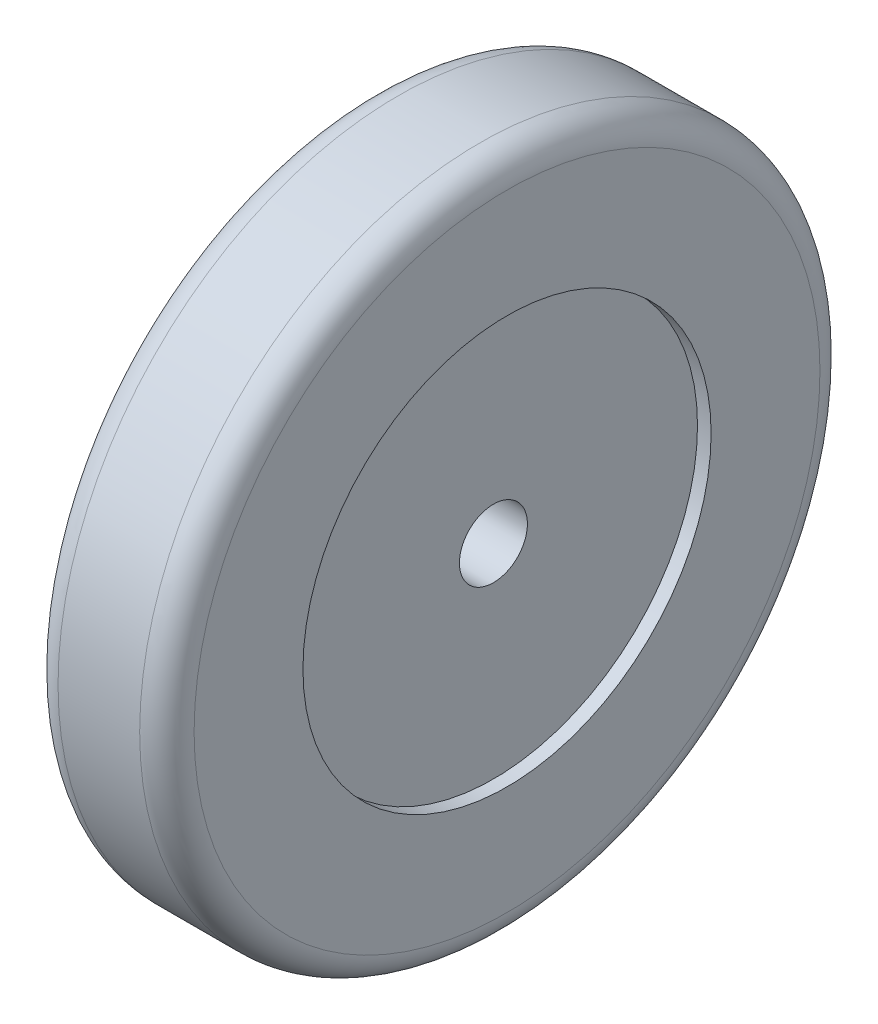
SolidWorks part; units mm, degrees
ref_plane "Front Plane" through (0, 0, 0) normal (0, 0, 1) x (1, 0, 0)
ref_plane "Top Plane" through (0, 0, 0) normal (0, 1, 0) x (1, 0, 0)
ref_plane "Right Plane" through (0, 0, 0) normal (1, 0, 0) x (0, 0, -1)
sketch "Sketch1" plane through (0, 0, 0) normal (1, 0, 0) x (0, 0, -1)
  circle A0 centre (0, 0) radius 31.75
  dimension "D1" = 63.5
extrude "Boss-Extrude1" add sketch "Sketch1" along normal mid plane 12.7
sketch "Sketch2" plane through (6.35, 0, 0) normal (1, 0, 0) x (0, 0, -1)
  circle A0 centre (0, 0) radius 3.175
  dimension "D1" = 6.35
extrude "Cut-Extrude1" cut sketch "Sketch2" against normal through all
fillet "Fillet1" radius 2.54 2 edges at (-6.35, 0, -31.75) (6.35, 0, -31.75)
sketch "Sketch3" plane through (6.35, 0, 0) normal (1, 0, 0) x (0, 0, -1)
  circle A0 centre (0, 0) radius 19.05
  dimension "D1" = 38.1
extrude "Cut-Extrude2" cut sketch "Sketch3" against normal blind 1.27
mirror "Mirror1" about plane through (0, 0, 0) normal (1, 0, 0) of "Cut-Extrude2"
